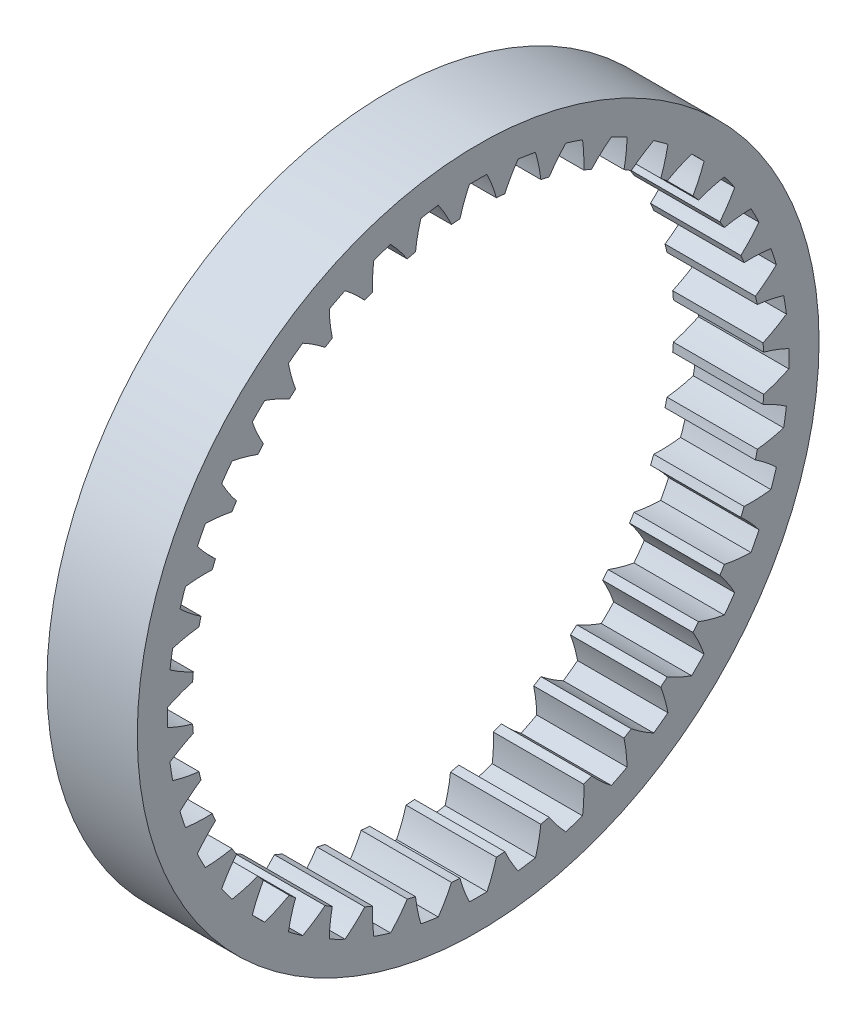
SolidWorks part; units mm, degrees
ref_plane "Plane1" through (0, 0, 0) normal (0, 0, 1) x (1, 0, 0)
ref_plane "Plane2" through (0, 0, 0) normal (0, 1, 0) x (1, 0, 0)
ref_plane "Plane3" through (0, 0, 0) normal (1, 0, 0) x (0, 0, -1)
sketch "HoldingSke" plane through (0, 0, 0) normal (0, 1, 0) x (1, 0, 0)
  line L0 (0, 0) -> (0.383, -0.3214)
  line L1 (-15, 0) -> (100, 0) construction
  line L2 (0, 0) -> (-2.1039, 2.3779)
  line L3 (0, 0) -> (-11.863, 4.5341)
  line L4 (0, 0) -> (6.6156, 5.5511)
  line L5 (0, 0) -> (-23.7986, -8.8762)
  line L6 (0, 0) -> (-10.5278, -7.1032)
  line L7 (-2.1039, 2.3779) -> (3.3635, 27.1825)
  line L8 (-76.2, 4.3779) -> (-54.61, 4.3779)
  line L9 (-71.009, 38.7566) -> (-53.1078, 45.2721)
  line L10 (-76.2, 71.12) -> (104.1128, 71.12)
  line L11 (0, 0) -> (-12, 0)
  line L12 (-76.2, 101.6) -> (-76.133, 101.6)
  line L13 (24.9733, 27.94) -> (52.9518, 28.4284)
  line L14 (24.9733, 27.94) -> (24.9743, 27.94)
  line L15 (24.9733, 27.94) -> (100.4006, 29.5858)
  circle A0 centre (0, 0) radius 12.5
  circle A1 centre (0, 0) radius 12.7
  circle A2 centre (0, 0) radius 12.7
  dimension "MHD" = 25.4
  dimension "Hub_dia" = 25.4
  dimension "Diameter" = 25
  dimension "Num_teeth" = 40
  dimension "Pitch" = 0.5
  dimension "Overall_len" = 25.4
  dimension "Show_teeth" = 40
  dimension "Thickness" = 12.7
  dimension "OAL" = 25.4001
  dimension "T_dim" = 21.59
  dimension "Ap" = 20
  dimension "H" = 19.05
  dimension "Pitch_radius" = 180.3128
  dimension "Width" = 12
  dimension "Backlash" = 0.067
  dimension "Addendum_fac" = 1
  dimension "Dedendum_fac" = 1.25
  dimension "Clearance_fac" = 0.25
  dimension "Dedendum_add" = 0.001
  dimension "Module" = 2
sketch "BasProSke" plane through (0, 0, 0) normal (0, 1, 0) x (1, 0, 0)
  line L0 (-10, 0) -> (60, 0) construction
  line L1 (0, 38) -> (0, 42.5264)
  line L2 (0, 38) -> (12, 38)
  line L3 (12, 38) -> (12, 42.5264)
  line L4 (12, 42.5264) -> (0, 42.5264)
  dimension "Thickness" = 12
  dimension "Diameter" = 85.0528
  dimension "Inside_diameter" = 76
revolve "Base-Revolve" add sketch "BasProSke" angle 360 about L0
sketch "TooCutSke" plane through (0, 0, 0) normal (1, 0, 0) x (0, 0, -1)
  line L3 (1.7379, 39.9622) -> (1.7379, 53.6633) construction
  line L4 (0, 0) -> (0, 59.563) construction
  line L5 (0, 0) -> (-5.3609, 68.1169) construction
  line L6 (-16.8604, 32.6066) -> (35.072, 36.6938) construction
  circle A0 centre (0, 0) radius 40 construction
  circle A1 centre (0, 0) radius 42.501 construction
  circle A2 centre (0, 0) radius 33.8289 construction
  circle A3 centre (0, 0) radius 37.9746 construction
  arc A4 (2.4273, 37.8969) -> (0.5225, 42.4978) centre (-16.8604, 32.6066) ccw
  arc A5 (2.4273, 37.8969) -> (-2.4273, 37.8969) centre (0, 0) ccw
  arc A6 (0.5225, 42.4978) -> (-0.5225, 42.4978) centre (0, 0) ccw
  arc A7 (-0.5225, 42.4978) -> (-2.4273, 37.8969) centre (16.8604, 32.6066) ccw
  dimension "Pitch_dia" = 80
  dimension "Base_dia" = 67.6579
  dimension "Root_dia" = 85.002
  dimension "Overcut_dia" = 75.9492
  dimension "Flank_rad" = 20
  dimension "Half_ang" = 4.5
  dimension "Half_CT" = 1.7379
extrude "ToothCut" cut sketch "TooCutSke" along normal through all
fillet "Breaks" [suppressed] radius 0.2
fillet "RootFillets" [suppressed] radius 0.501
pattern_circular "TeethCuts" count 40 every 9 about axis through (-10, 0, 0) along (1, 0, 0) of "RootFillets", "Breaks", "ToothCut"
sketch "Sketch1" plane through (0, 0, 0) normal (1, 0, 0) x (0, 0, -1)
  circle A0 centre (0, 0) radius 41.2764
extrude "Extrude-Thin1" add sketch "Sketch1" along normal through all thin
scale "Scale1" scale about origin uniform scaling yes scale factor 0.4
equation "' \"Module@HoldingSke\" = 6.35"
equation "' \"Num_teeth@HoldingSke\" = 24"
equation "' \"Ap@HoldingSke\" =  14.5"
equation "' \"Ap@HoldingSke\" = 14.5"
equation "' \"Width@HoldingSke\" = 12"
equation "' \"Diameter@HoldingSke\" = 8 * 25.4"
equation "' \"Show_teeth@HoldingSke\" = 100"
equation "' \"Backlash@HoldingSke\" = 0.009 * 25.4"
equation "' \"Addendum_fac@HoldingSke\" = 1.0"
equation "' \"Dedendum_fac@HoldingSke\" = 1.25"
equation "' \"Dedendum_add@HoldingSke\" = 0.00005 * 25.4"
equation "' \"Clearance_fac@HoldingSke\" = 0.25"
equation "\"Pitch@HoldingSke\" = 1 / \"Module@HoldingSke\" "
equation "\"Overcut_dia@TooCutSke\" = (\"Num_teeth@HoldingSke\" - 2 * \"Addendum_fac@HoldingSke\") / \"Pitch@HoldingSke\" - 0.002 * 25.4"
equation "\"Pitch_dia@TooCutSke\" = \"Num_teeth@HoldingSke\" / \"Pitch@HoldingSke\""
equation "\"Base_dia@TooCutSke\" = \"Num_teeth@HoldingSke\" / \"Pitch@HoldingSke\" * cos((\"Ap@HoldingSke\"  * 3.14159265 / 180)) * 0.90"
equation "\"Root_dia@TooCutSke\" = \"Num_teeth@HoldingSke\"  / \"Pitch@HoldingSke\" + 2 *  \"Dedendum_fac@HoldingSke\"/ \"Pitch@HoldingSke\" + \"Dedendum_add@HoldingSke\" * 2"
equation "\"Half_ang@TooCutSke\" = 180 / \"Num_teeth@HoldingSke\""
equation "\"Half_CT@TooCutSke\" = \"Num_teeth@HoldingSke\" / \"Pitch@HoldingSke\" * sin((3.14159265 / 2 / \"Num_teeth@HoldingSke\")) / 2 + 10 * \"Backlash@HoldingSke\" / 4"
equation "\"Flank_rad@TooCutSke\" = \"Num_teeth@HoldingSke\" / \"Pitch@HoldingSke\" / 4"
equation "\"Radius@RootFillets\"= \"Clearance_fac@HoldingSke\" / \"Pitch@HoldingSke\" + \"Dedendum_add@HoldingSke\""
equation "\"Break_rad@Breaks\" = 0.02 / \"Pitch@HoldingSke\" * 5"
equation "\"Num_teeth@TeethCuts\" = int( \"Show_teeth@HoldingSke\" ) + 1"
equation "\"Num_teeth@TeethCuts\" = ((sgn( \"Num_teeth@TeethCuts\" - \"Num_teeth@HoldingSke\" )-1)*( \"Num_teeth@TeethCuts\" - \"Num_teeth@HoldingSke\" ))/-2+ \"Num_teeth@HoldingSke\""
equation "\"Num_teeth@TeethCuts\" = ((sgn( \"Num_teeth@TeethCuts\" - 2.0)+1)*( \"Num_teeth@TeethCuts\" - 2.0))/2 +2.0"
equation "\"Angle@TeethCuts\" = 360.0 / \"Num_teeth@HoldingSke\""
equation "\"Diameter@BasProSke\" = \"Num_teeth@HoldingSke\"  / \"Pitch@HoldingSke\" + 2 *  \"Dedendum_fac@HoldingSke\"/ \"Pitch@HoldingSke\" + \"Dedendum_add@HoldingSke\" * 2 + 0.002 * 25.4"
equation "\"Diameter@BasProSke\" = ((sgn( \"Diameter@BasProSke\"  - \"Diameter@HoldingSke\" )+1)*( \"Diameter@BasProSke\"  - \"Diameter@HoldingSke\" ))/2 + \"Diameter@HoldingSke\""
equation "\"Inside_diameter@BasProSke\" =  (\"Num_teeth@HoldingSke\" - 2 * \"Addendum_fac@HoldingSke\") / \"Pitch@HoldingSke\" "
equation "\"Thickness@BasProSke\"  = \"Width@HoldingSke\""
